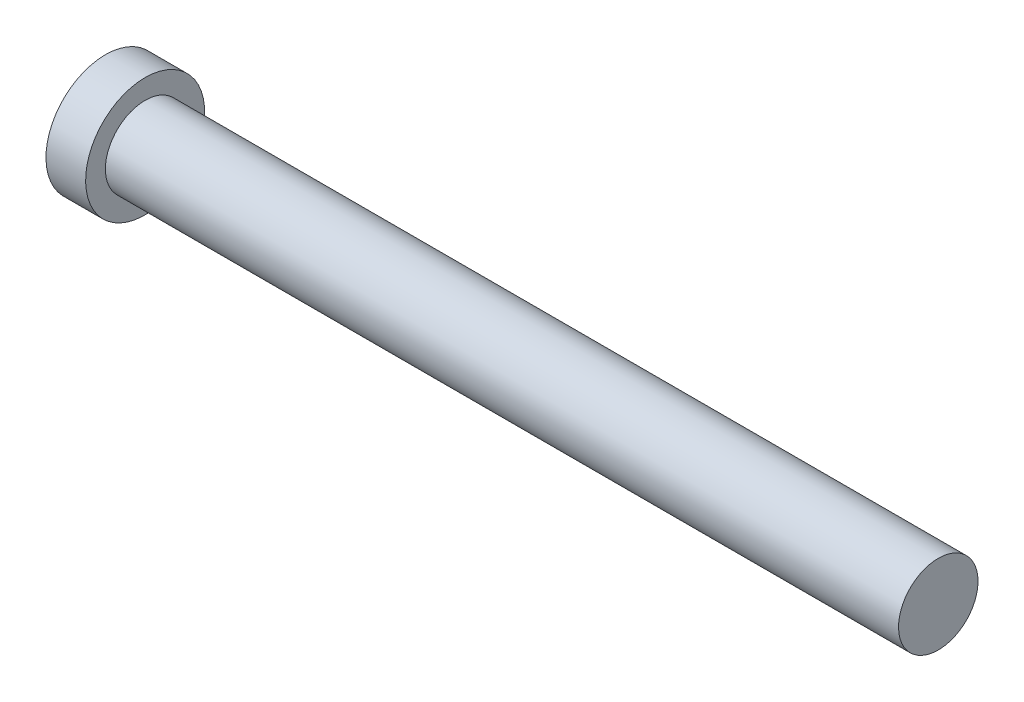
SolidWorks part; units mm, degrees
ref_plane "Front Plane" through (0, 0, 0) normal (0, 0, 1) x (1, 0, 0)
ref_plane "Top Plane" through (0, 0, 0) normal (0, 1, 0) x (1, 0, 0)
ref_plane "Right Plane" through (0, 0, 0) normal (1, 0, 0) x (0, 0, -1)
sketch "Sketch1" plane through (0, 0, 0) normal (0, 0, 1) x (1, 0, 0)
  line L0 (0, 0) -> (0, 9.525)
  line L5 (0, 9.525) -> (6.35, 9.525)
  line L6 (6.35, 9.525) -> (6.35, 6.3627)
  line L7 (6.35, 6.3627) -> (133.35, 6.3627)
  line L8 (133.35, 6.3627) -> (133.35, 0)
  line L9 (133.35, 0) -> (0, 0)
  dimension "D1" = 6.35
  dimension "D2" = 6.3627
  dimension "D3" = 9.525
  dimension "D4" = 127
revolve "Revolve1" add sketch "Sketch1" angle 360 about L9
